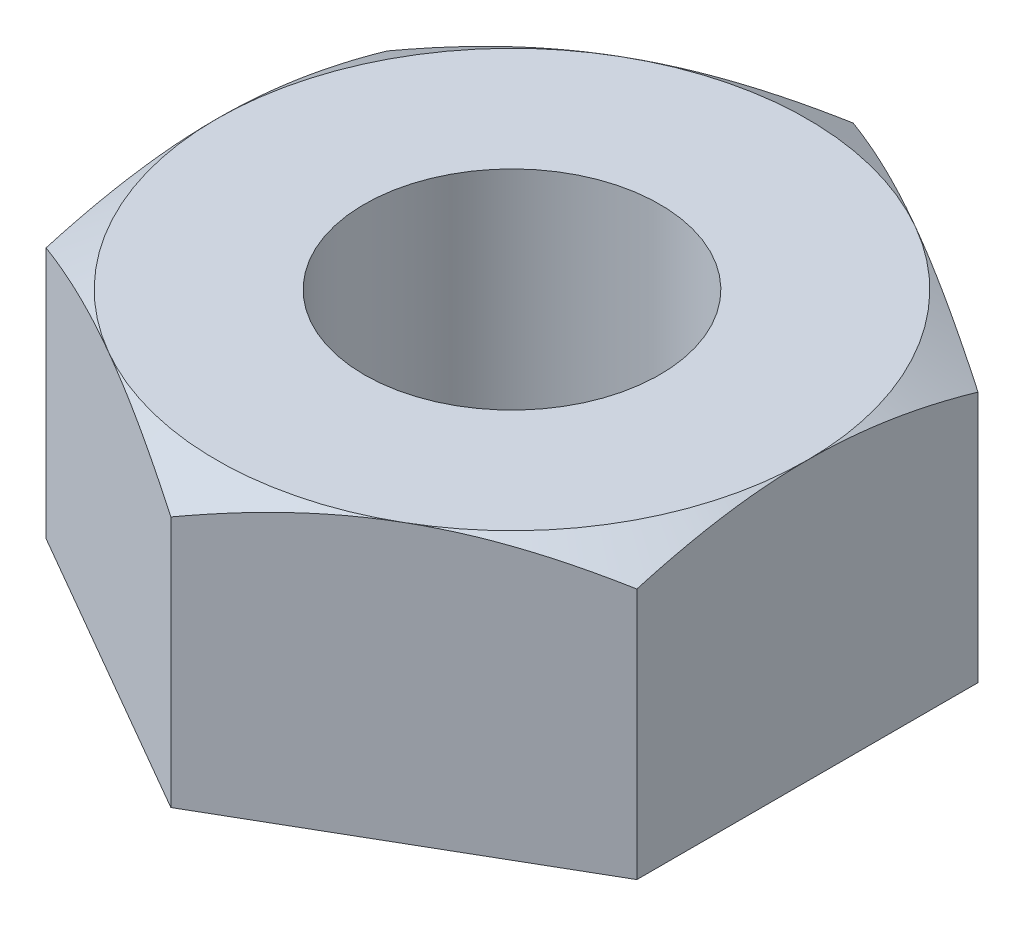
SolidWorks part; units mm, degrees
ref_plane "Front Plane" through (0, 0, 0) normal (0, 0, 1) x (1, 0, 0)
ref_plane "Top Plane" through (0, 0, 0) normal (0, 1, 0) x (1, 0, 0)
ref_plane "Right Plane" through (0, 0, 0) normal (1, 0, 0) x (0, 0, -1)
sketch "Sketch1" plane through (0, 0, 0) normal (0, 1, 0) x (1, 0, 0)
  line L1 (0, 9.815) -> (-8.5, 4.9075)
  line L2 (-8.5, 4.9075) -> (-8.5, -4.9075)
  line L3 (-8.5, -4.9075) -> (0, -9.815)
  line L4 (0, -9.815) -> (8.5, -4.9075)
  line L5 (8.5, -4.9075) -> (8.5, 4.9075)
  line L6 (8.5, 4.9075) -> (0, 9.815)
  circle A0 centre (0, 0) radius 8.5 construction
  dimension "NT_S" = 17
extrude "Boss-Extrude1" add sketch "Sketch1" against normal blind 8
sketch "Sketch2" plane through (0, 0, 0) normal (1, 0, 0) x (0, 0, -1)
  line L0 (0, 0) -> (0, -8) construction
  line L1 (-4.9075, -8) -> (4.9075, -8) construction
  line L2 (8.5, 0) -> (9.815, 0)
  line L3 (9.815, 0) -> (9.815, -0.7592)
  line L4 (9.815, -0.7592) -> (8.5, 0)
  line L5 (4.9075, 0) -> (9.815, 0) construction
  line L6 (9.815, -8) -> (9.815, 0) construction
  dimension "D1" = 30
revolve "Cut-Revolve1" cut sketch "Sketch2" angle 360 about L0
hole_wizard "Tapped Hole1" positions "Sketch4" profile "Sketch3" tap size "M3x0.5" standard "JIS" end condition through all
sketch "Sketch4" plane through (0, 0, 0) normal (0, 1, 0) x (1, 0, 0)
  point P0 (0, 0)
sketch "Sketch3" plane through (0, 0, 0) normal (1, 0, 0) x (0, 0, 1)
  line L0 (0, 0) -> (0, 8)
  line L1 (0, 8) -> (4.25, 8)
  line L2 (4.25, 8) -> (4.25, 0)
  line L5 (4.25, 0) -> (0, 0)
  line L11 (0, 0) -> (0, 8) construction
  dimension "Thru Tap Drill Dia." = 8.5
  dimension "Thru Tap Drill Depth" = 8
cosmetic thread "Hole Thread1" parameters "NT_M"=10
